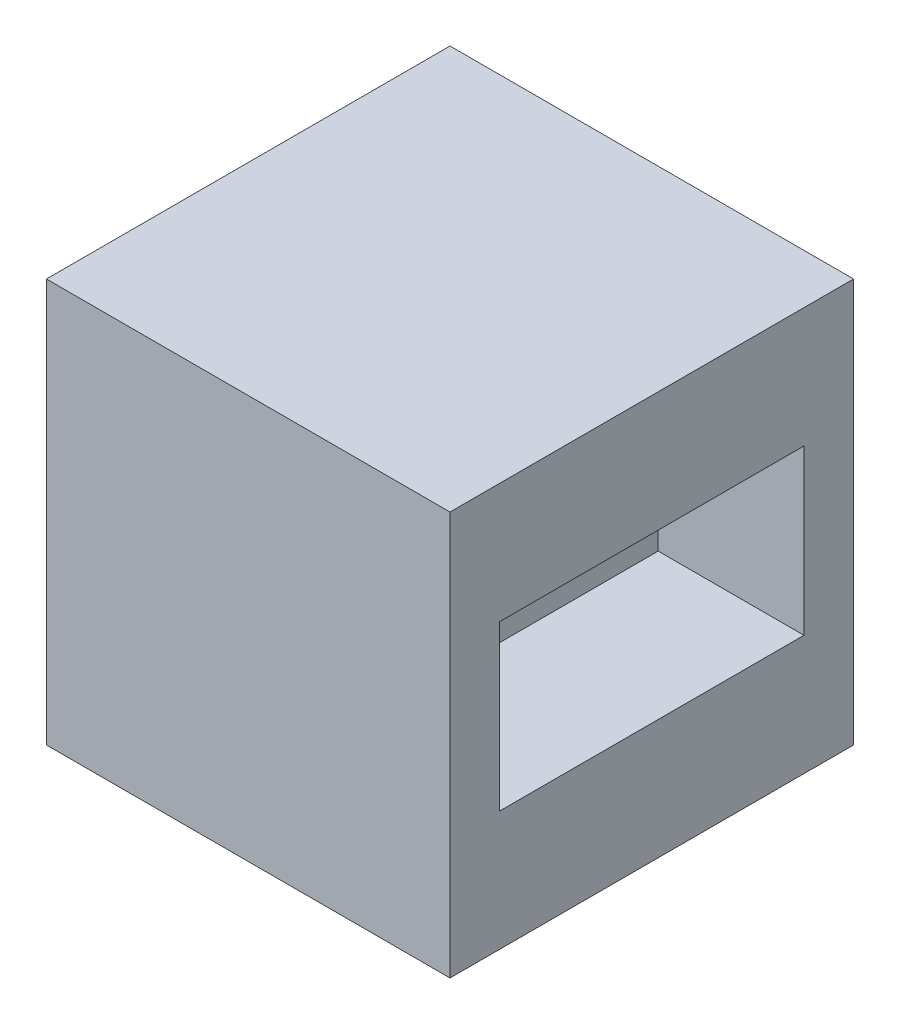
SolidWorks part; units mm, degrees
ref_plane "Front Plane" through (0, 0, 0) normal (0, 0, 1) x (1, 0, 0)
ref_plane "Top Plane" through (0, 0, 0) normal (0, 1, 0) x (1, 0, 0)
ref_plane "Right Plane" through (0, 0, 0) normal (1, 0, 0) x (0, 0, -1)
sketch "Sketch1" plane through (0, 0, 0) normal (0, 0, 1) x (1, 0, 0)
  line L1 (0, 0) -> (30, 0)
  line L2 (0, 0) -> (0, -30)
  line L3 (0, -30) -> (30, -30)
  line L4 (30, 0) -> (30, -30)
  dimension "D1" = 30
  dimension "D2" = 30
extrude "Boss-Extrude1" add sketch "Sketch1" along normal blind 30
sketch "Sketch2" plane through (30, 0, 0) normal (1, 0, 0) x (0, 0, -1)
  line L0 (-15, 0) -> (-15, -30) construction
  line L1 (-30, 0) -> (0, 0) construction
  line L2 (-30, -30) -> (0, -30) construction
  line L3 (-30, -15) -> (0, -15) construction
  line L4 (-30, -30) -> (-30, 0) construction
  line L5 (0, -30) -> (0, 0) construction
  line L6 (-26.315, -8.905) -> (-26.315, -21.095)
  line L7 (-26.315, -15) -> (-3.685, -15)
  line L8 (-15, -15) -> (-15, -21.095)
  line L9 (-26.315, -21.095) -> (-3.685, -21.095)
  line L10 (-3.685, -8.905) -> (-3.685, -21.095)
  line L11 (-26.315, -8.905) -> (-3.685, -8.905)
  dimension "D1" = 11.315
  dimension "D2" = 6.095
extrude "Cut-Extrude1" cut sketch "Sketch2" against normal blind 10.84 contours L6 L9 L8 L7 | L11 L6 L7 L10 | L10 L7 L8 L9
sketch "Sketch3" plane through (0, -30, 0) normal (0, -1, 0) x (1, 0, 0)
  line L0 (15, 30) -> (15, 0) construction
  line L1 (0, 30) -> (30, 30) construction
  line L2 (0, 0) -> (30, 0) construction
  line L3 (0, 15) -> (30, 15) construction
  line L4 (0, 30) -> (0, 0) construction
  line L5 (30, 30) -> (30, 0) construction
  line L11 (4.938, 18.2941) -> (24.938, 18.2941)
  line L12 (4.938, 18.2941) -> (4.938, 12.2941)
  line L13 (4.938, 12.2941) -> (24.938, 12.2941)
  line L14 (24.938, 18.2941) -> (24.938, 12.2941)
  dimension "D1" = 20
  dimension "D2" = 6
extrude "Cut-Extrude4" cut sketch "Sketch3" against normal blind 2
